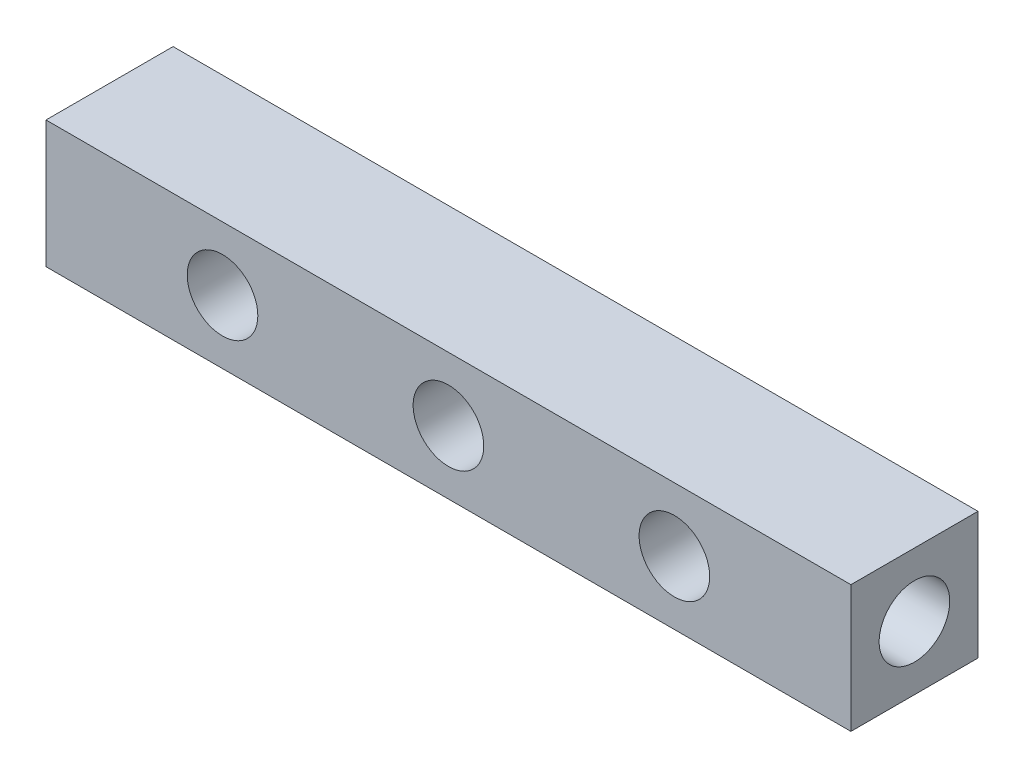
SolidWorks part; units mm, degrees
ref_plane "Front Plane" through (0, 0, 0) normal (0, 0, 1) x (1, 0, 0)
ref_plane "Top Plane" through (0, 0, 0) normal (0, 1, 0) x (1, 0, 0)
ref_plane "Right Plane" through (0, 0, 0) normal (1, 0, 0) x (0, 0, -1)
sketch "Sketch1" plane through (0, 0, 0) normal (0, 0, 1) x (1, 0, 0)
  line L1 (-28.5, 39.75) -> (0, 39.75)
  line L2 (-28.5, 39.75) -> (-28.5, 35.25)
  line L3 (-28.5, 35.25) -> (0, 35.25)
  line L4 (0, 39.75) -> (0, 35.25)
  dimension "D1" = 4.5
  dimension "D2" = 28.5
extrude "Boss-Extrude1" add sketch "Sketch1" along normal blind 4.5 contours L3 L4 L1 L2
hole_wizard "Side Shaft Holes (M3)" positions "Sketch3" profile "Sketch2" tap size "M3x0.5" standard "ANSI Metric"
sketch "Sketch3" plane through (0, 0, 0) normal (1, 0, 0) x (0, 0, -1)
  line L0 (0, 35.25) -> (-4.5, 39.75) construction
  line L3 (-4.5, 35.25) -> (0, 35.25) construction
  line L4 (-4.5, 39.75) -> (-4.5, 35.25) construction
  line L5 (-4.5, 35.25) -> (0, 35.25) construction
  line L6 (-4.5, 39.75) -> (-4.5, 35.25) construction
  point P6 (-2.25, 37.5)
  point P26 (45.3129, 37.5)
sketch "Sketch2" plane through (0, 37.5, 2.25) normal (0, 1, 0) x (0, 0, -1)
  line L0 (0, 0) -> (0, 4)
  line L1 (0, 4) -> (1.25, 3.2489)
  line L2 (1.25, 3.2489) -> (1.25, 0)
  line L5 (1.25, 0) -> (0, 0)
  line L10 (0, 4) -> (-1.25, 3.2489) construction
  line L11 (0, -6.35) -> (0, 107.95) construction
  dimension "Tap Drill Dia." = 2.5
  dimension "Tap Drill Depth" = 4
  dimension "Drill Angle" = 118
cosmetic thread "Hole Thread1"
ref_plane "Midplane" through (-14.25, 0, 0) normal (-1, 0, 0) x (0, 0, 1)
mirror "Shaft Hole Mirror" about plane through (-14.25, 0, 0) normal (-1, 0, 0) of "Side Shaft Holes (M3)"
cosmetic thread "Hole Thread2"
hole_wizard "M3x0.5 Tapped Hole3" positions "Sketch6" profile "Sketch7" tap size "M3x0.5" standard "ANSI Metric" end condition through all
sketch "Sketch6" plane through (0, 0, 4.5) normal (0, 0, 1) x (1, 0, 0)
  line L0 (-4, 37.5) -> (-3.2489, 36.25) construction
  line L1 (-3.2489, 38.75) -> (-4, 37.5) construction
  line L2 (-25.2511, 36.25) -> (-24.5, 37.5) construction
  line L3 (-24.5, 37.5) -> (-25.2511, 38.75) construction
  line L4 (-4, 37.5) -> (-3.2489, 36.25) construction
  line L5 (-3.2489, 38.75) -> (-4, 37.5) construction
  line L6 (-25.2511, 36.25) -> (-24.5, 37.5) construction
  line L7 (-24.5, 37.5) -> (-25.2511, 38.75) construction
  line L8 (-24.5, 37.5) -> (-24.5, 45.5788) construction
  line L10 (-4, 37.5) -> (-4, 44.8277) construction
  line L13 (-24.5, 37.5) -> (-22.25, 37.5) construction
  line L14 (-22.25, 37.5) -> (-14.25, 37.5) construction
  line L15 (-14.25, 37.5) -> (-6.25, 37.5) construction
  line L16 (-6.25, 37.5) -> (-4, 37.5) construction
  line L18 (-24.5, 39.75) -> (-4, 39.75) construction
  line L19 (-28.5, 39.75) -> (0, 39.75) construction
  point P27 (-14.25, 37.5)
  point P29 (-22.25, 37.5)
  point P31 (-6.25, 37.5)
  point P53 (-14.25, 39.75)
  dimension "D1" = 8
sketch "Sketch7" plane through (-6.25, 37.5, 4.5) normal (1, 0, 0) x (0, -1, 0)
  line L0 (0, 0) -> (0, 4.5)
  line L1 (0, 4.5) -> (1.25, 4.5)
  line L2 (1.25, 4.5) -> (1.25, 0)
  line L5 (1.25, 0) -> (0, 0)
  line L11 (0, -6.35) -> (0, 107.95) construction
  dimension "Thru Tap Drill Dia." = 2.5
  dimension "Thru Tap Drill Depth" = 4.5
cosmetic thread "Hole Thread3"
cosmetic thread "Hole Thread4"
cosmetic thread "Hole Thread5"
